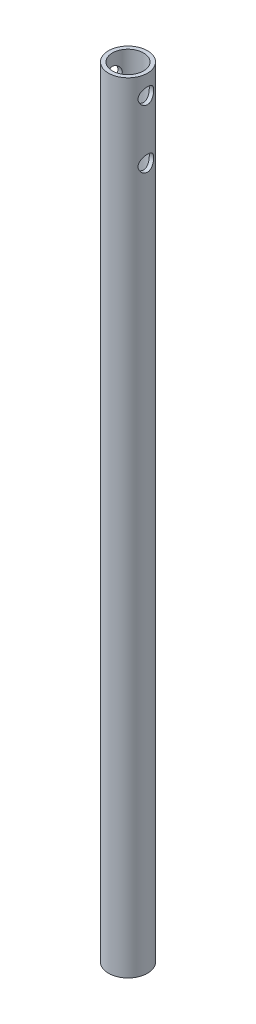
SolidWorks part; units mm, degrees
ref_plane "前视基准面" through (0, 0, 0) normal (0, 0, 1) x (1, 0, 0)
ref_plane "上视基准面" through (0, 0, 0) normal (0, 1, 0) x (1, 0, 0)
ref_plane "右视基准面" through (0, 0, 0) normal (1, 0, 0) x (0, 0, -1)
sketch "草图2" plane through (0, 0, 0) normal (0, 1, 0) x (1, 0, 0)
  circle A0 centre (0, 0) radius 3
  circle A1 centre (0, 0) radius 1.5
extrude "凸台-拉伸1" add sketch "草图2" along normal blind 200
sketch "草图3" plane through (0, 200, 0) normal (0, 1, 0) x (1, 0, 0)
  circle A0 centre (0, 0) radius 5
extrude "凸台-拉伸2" add sketch "草图3" against normal blind 200
sketch "草图4" plane through (0, 200, 0) normal (0, 1, 0) x (1, 0, 0)
  circle A0 centre (0, 0) radius 4
extrude "切除-拉伸1" cut sketch "草图4" against normal blind 200
sketch "草图5" plane through (0, 0, 0) normal (1, 0, 0) x (0, 0, -1)
  line L0 (0, 200) -> (0, 195)
  line L1 (5, 200) -> (-5, 200) construction
  line L2 (0, 195) -> (0, 180)
  circle A0 centre (0, 195) radius 2
  circle A1 centre (0, 180) radius 2
extrude "切除-拉伸5" cut sketch "草图5" against normal mid plane 200 contours A1 | A0
